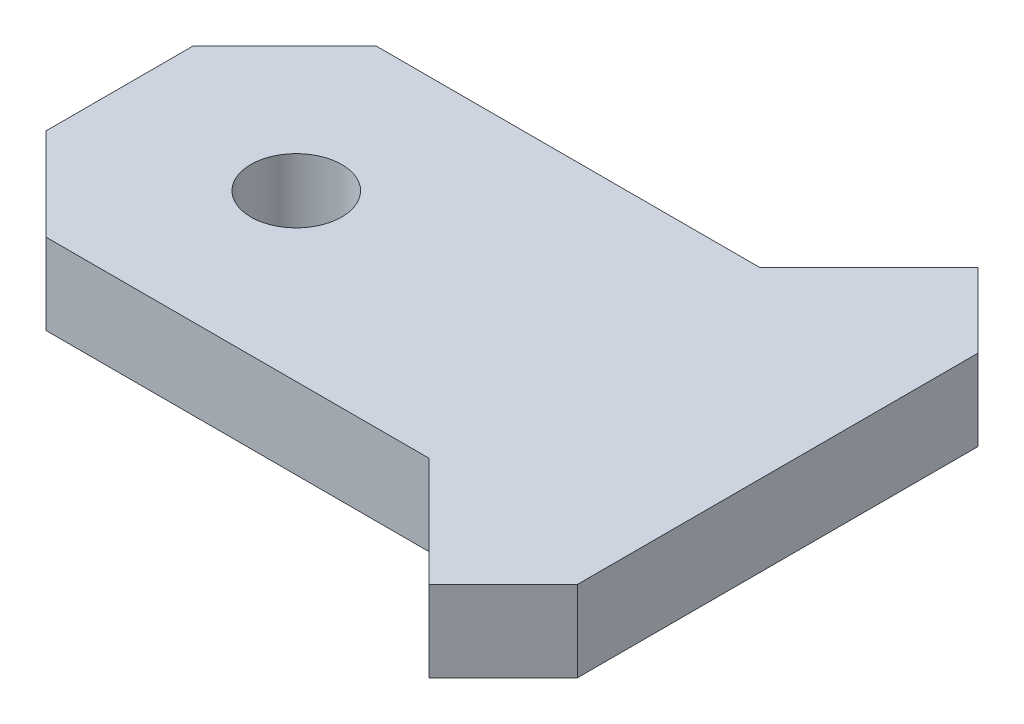
SolidWorks part; units mm, degrees
ref_plane "Front Plane" through (0, 0, 0) normal (0, 0, 1) x (1, 0, 0)
ref_plane "Top Plane" through (0, 0, 0) normal (0, 1, 0) x (1, 0, 0)
ref_plane "Right Plane" through (0, 0, 0) normal (1, 0, 0) x (0, 0, -1)
sketch "Sketch1" plane through (0, 0, 0) normal (0, 1, 0) x (1, 0, 0)
  line L0 (0, 3.6244) -> (0, -3.6244)
  line L1 (0, -3.6244) -> (5.1256, -8.75) construction
  line L2 (5.1256, -8.75) -> (24.0529, -8.75) construction
  line L3 (24.0529, -8.75) -> (28.8794, -13.5765)
  line L4 (28.8794, -13.5765) -> (32.5563, -9.8995)
  line L5 (32.5563, -9.8995) -> (32.5563, 9.8995)
  line L6 (32.5563, 9.8995) -> (28.8794, 13.5765)
  line L7 (28.8794, 13.5765) -> (24.0529, 8.75)
  line L8 (24.0529, 8.75) -> (5.1256, 8.75) construction
  line L9 (5.1256, 8.75) -> (0, 3.6244) construction
  line L10 (0, 0) -> (8.75, 0) construction
  line L11 (0, 3.6244) -> (4.558, 8.1823) construction
  line L12 (4.558, 8.1823) -> (23.4853, 8.1823) construction
  line L13 (23.4853, 8.1823) -> (24.0529, 8.75)
  line L14 (0, -3.6244) -> (4.558, -8.1823) construction
  line L15 (4.558, -8.1823) -> (23.4853, -8.1823) construction
  line L16 (23.4853, -8.1823) -> (24.0529, -8.75)
  line L17 (0, 3.6244) -> (4.548, 8.1723)
  line L18 (4.548, 8.1723) -> (23.4753, 8.1723)
  line L19 (23.4753, 8.1723) -> (23.4853, 8.1823)
  line L20 (0, -3.6244) -> (4.548, -8.1723)
  line L21 (4.548, -8.1723) -> (23.4753, -8.1723)
  line L22 (23.4753, -8.1723) -> (23.4853, -8.1823)
  circle A0 centre (8.75, 0) radius 2.25
  point P10 (0, 0)
  point P23 (22.0836, 6.7807)
  dimension "D6" = 4.5
  dimension "D1" = 45
  dimension "D2" = 45
  dimension "D3" = 135
  dimension "D4" = 135
  dimension "D5" = 17.5
  dimension "D7" = 8.75
  dimension "D8" = 7.6284
  dimension "D9" = 5.2
  dimension "D10" = 16.3647
  dimension "D11" = 23.4853
  dimension "D12" = 0.01
extrude "Boss-Extrude1" add sketch "Sketch1" along normal blind 4
